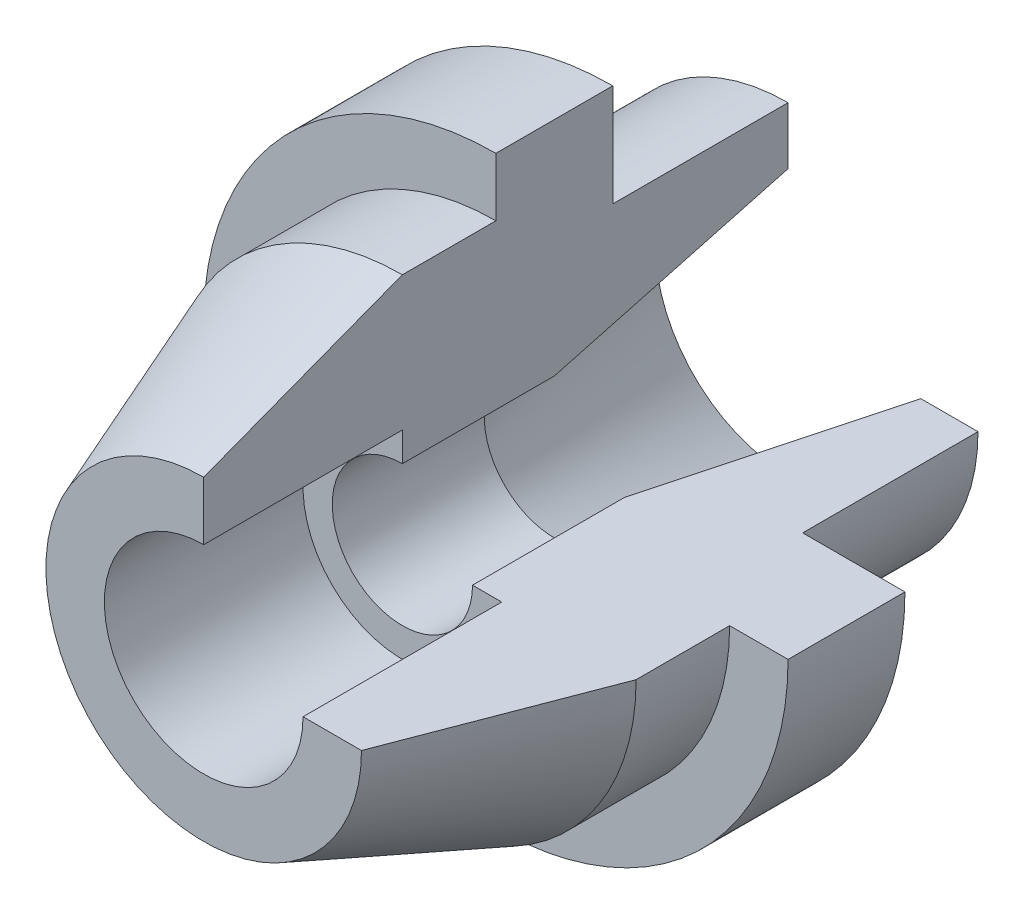
SolidWorks part; units mm, degrees
ref_plane "Front Plane" through (0, 0, 0) normal (0, 0, 1) x (1, 0, 0)
ref_plane "Top Plane" through (0, 0, 0) normal (0, 1, 0) x (1, 0, 0)
ref_plane "Right Plane" through (0, 0, 0) normal (1, 0, 0) x (0, 0, -1)
sketch "Sketch1" plane through (0, 0, 0) normal (1, 0, 0) x (0, 0, -1)
  line L0 (0, 0) -> (0, 27)
  line L1 (0, 27) -> (34, 40)
  line L2 (34, 40) -> (50, 40)
  line L3 (50, 40) -> (50, 50)
  line L4 (50, 50) -> (70, 50)
  line L5 (70, 50) -> (70, 32.5)
  line L6 (70, 32.5) -> (100, 32.5)
  line L7 (100, 32.5) -> (100, 0)
  line L8 (100, 0) -> (0, 0)
  dimension "D1" = 32.5
  dimension "D2" = 50
  dimension "D3" = 40
  dimension "D4" = 27
  dimension "D5" = 34
  dimension "D6" = 20
  dimension "D7" = 30
  dimension "D8" = 100
revolve "Revolve1" add sketch "Sketch1" angle 270 about L8
sketch "Sketch2" plane through (0, 0, 0) normal (1, 0, 0) x (0, 0, -1)
  line L0 (0, 17) -> (0, 0)
  line L1 (0, 0) -> (100, 0)
  line L2 (100, 0) -> (100, 22.718)
  line L3 (100, 22.718) -> (60, 12)
  line L4 (60, 12) -> (34, 12)
  line L5 (34, 12) -> (34, 17)
  line L6 (34, 17) -> (0, 17)
  line L7 (100, 0) -> (100, 32.5) construction
  point P3 (100, 23.6971)
  point P11 (17, 17)
  dimension "D1" = 15
  dimension "D2" = 60
  dimension "D3" = 34
  dimension "D4" = 17
  dimension "D5" = 12
revolve "Cut-Revolve1" cut sketch "Sketch2" angle 360 about L1
